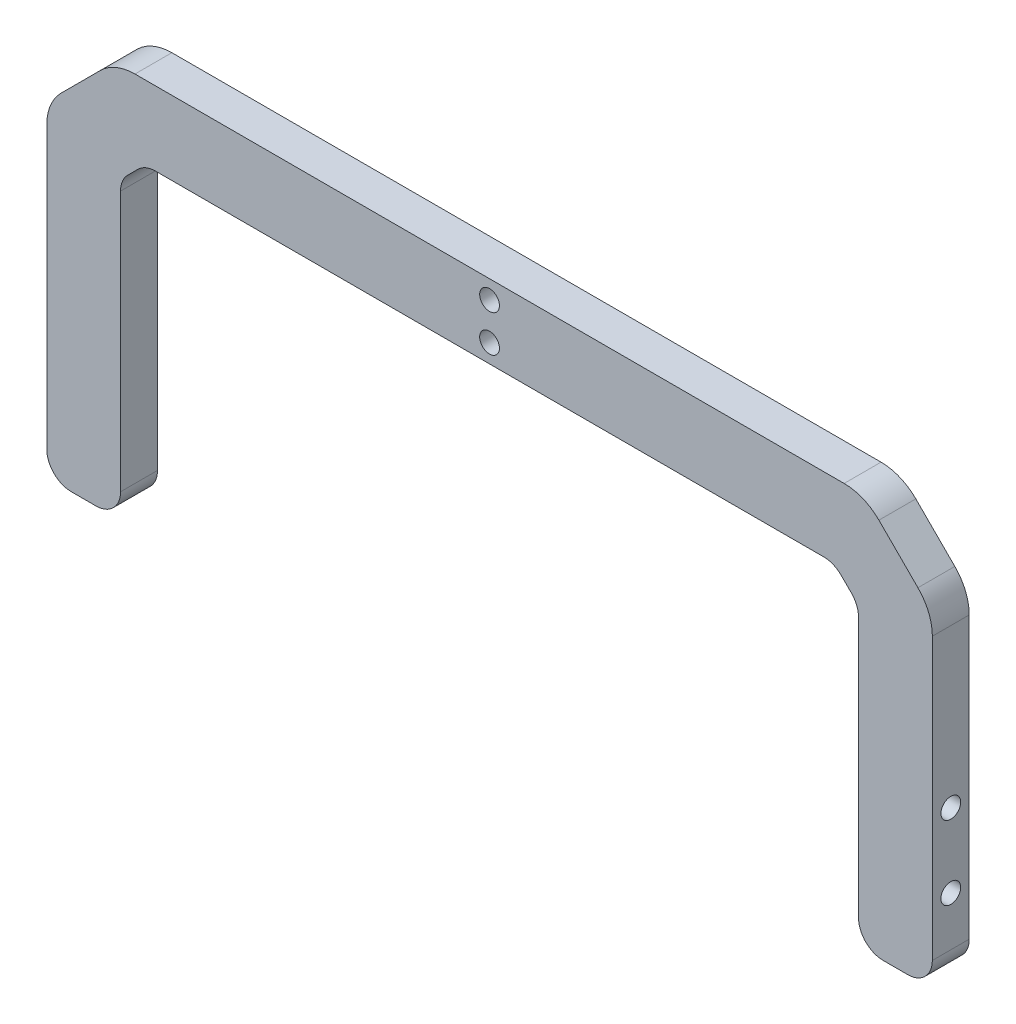
SolidWorks part; units mm, degrees
material "6061-T6 (SS)"
ref_plane "Front Plane" through (0, 0, 0) normal (0, 0, 1) x (1, 0, 0)
ref_plane "Top Plane" through (0, 0, 0) normal (0, 1, 0) x (1, 0, 0)
ref_plane "Right Plane" through (0, 0, 0) normal (1, 0, 0) x (0, 0, -1)
sketch "Sketch1" plane through (0, 0, 0) normal (0, 0, 1) x (1, 0, 0)
  line L12 (-114.3, -17.5092) -> (-96.7908, 0)
  line L17 (-96.7908, 0) -> (96.7908, 0)
  line L18 (96.7908, 0) -> (114.3, -17.5092)
  line L19 (114.3, -17.5092) -> (114.3, -101.6)
  line L20 (114.3, -101.6) -> (95.25, -101.6)
  line L21 (95.25, -101.6) -> (95.25, -25.4)
  line L22 (95.25, -25.4) -> (88.9, -19.05)
  line L23 (88.9, -19.05) -> (-88.9, -19.05)
  line L24 (-88.9, -19.05) -> (-95.25, -25.4)
  line L25 (-95.25, -25.4) -> (-95.25, -101.6)
  line L26 (-95.25, -101.6) -> (-114.3, -101.6)
  line L27 (-114.3, -101.6) -> (-114.3, -17.5092)
  line L28 (0, 0) -> (0, 47.6788) construction
  line L29 (0, 0) -> (0, -19.05) construction
  dimension "D1" = 101.6
  dimension "D2" = 228.6
  dimension "D3" = 19.05
  dimension "D4" = 19.05
  dimension "D5" = 45
  dimension "D6" = 76.2
  dimension "D7" = 19.05
extrude "Boss-Extrude1" add sketch "Sketch1" along normal blind 9.525
fillet "Fillet3" radius 6.35 8 edges at (95.25, -25.4, 4.7625) (88.9, -19.05, 4.7625) (-88.9, -19.05, 4.7625) (-95.25, -25.4, 4.7625) (114.3, -101.6, 4.7625) (95.25, -101.6, 4.7625) (-114.3, -101.6, 4.7625) (-95.25, -101.6, 4.7625)
fillet "Fillet1" radius 12.7 4 edges at (96.7908, 0, 4.7625) (114.3, -17.5092, 4.7625) (-114.3, -17.5092, 4.7625) (-96.7908, 0, 4.7625)
hole_wizard "1/4-20 Tapped Hole1" positions "Sketch2" profile "Sketch3" tap size "1/4-20" standard "ANSI Inch" end condition through all
sketch "Sketch2" plane through (0, 0, 9.525) normal (0, 0, 1) x (1, 0, 0)
  line L0 (0, 0) -> (0, -4.7625) construction
  line L1 (0, -4.7625) -> (0, -14.2875) construction
  line L2 (0, -14.2875) -> (0, -19.05) construction
  line L6 (-86.2697, -19.05) -> (86.2697, -19.05) construction
  point P0 (0, -4.7625)
  point P2 (0, -14.2875)
  dimension "D1" = 4.7625
sketch "Sketch3" plane through (0, -4.7625, 9.525) normal (1, 0, 0) x (0, -1, 0)
  line L0 (0, 0) -> (0, 9.525)
  line L1 (0, 9.525) -> (2.5527, 9.525)
  line L2 (2.5527, 9.525) -> (2.5527, 0)
  line L5 (2.5527, 0) -> (0, 0)
  line L11 (0, -6.35) -> (0, 107.95) construction
  dimension "Thru Tap Drill Dia." = 5.1054
  dimension "Thru Tap Drill Depth" = 9.525
cosmetic thread "Hole Thread3" parameters "D2"=6.35
cosmetic thread "Hole Thread4" parameters "D2"=6.35
hole_wizard "1/4-20 Tapped Hole2" positions "Sketch4" profile "Sketch5" tap size "1/4-20" standard "ANSI Inch"
sketch "Sketch4" plane through (114.3, 0, 0) normal (1, 0, 0) x (0, 0, -1)
  line L0 (-4.7625, -101.6) -> (-4.7625, -82.55) construction
  line L1 (0, -101.6) -> (-9.525, -101.6) construction
  line L2 (-4.7625, -82.55) -> (-4.7625, -63.5) construction
  point P0 (-4.7625, -82.55)
  point P2 (-4.7625, -63.5)
  dimension "D1" = 19.05
  dimension "D2" = 19.05
sketch "Sketch5" plane through (114.3, -82.55, 4.7625) normal (0, 1, 0) x (0, 0, -1)
  line L0 (0, 0) -> (0, 17.4088)
  line L1 (0, 17.4088) -> (2.5527, 15.875)
  line L2 (2.5527, 15.875) -> (2.5527, 0)
  line L5 (2.5527, 0) -> (0, 0)
  line L10 (0, 17.4088) -> (-2.5527, 15.875) construction
  line L11 (0, -6.35) -> (0, 107.95) construction
  dimension "Tap Drill Dia." = 5.1054
  dimension "Tap Drill Depth" = 15.875
  dimension "Drill Angle" = 118
cosmetic thread "Hole Thread5" parameters "D1"=12.7, "D2"=6.35
cosmetic thread "Hole Thread6" parameters "D1"=12.7, "D2"=6.35
mirror "Mirror1" about plane through (0, 0, 0) normal (1, 0, 0) of "1/4-20 Tapped Hole2"
